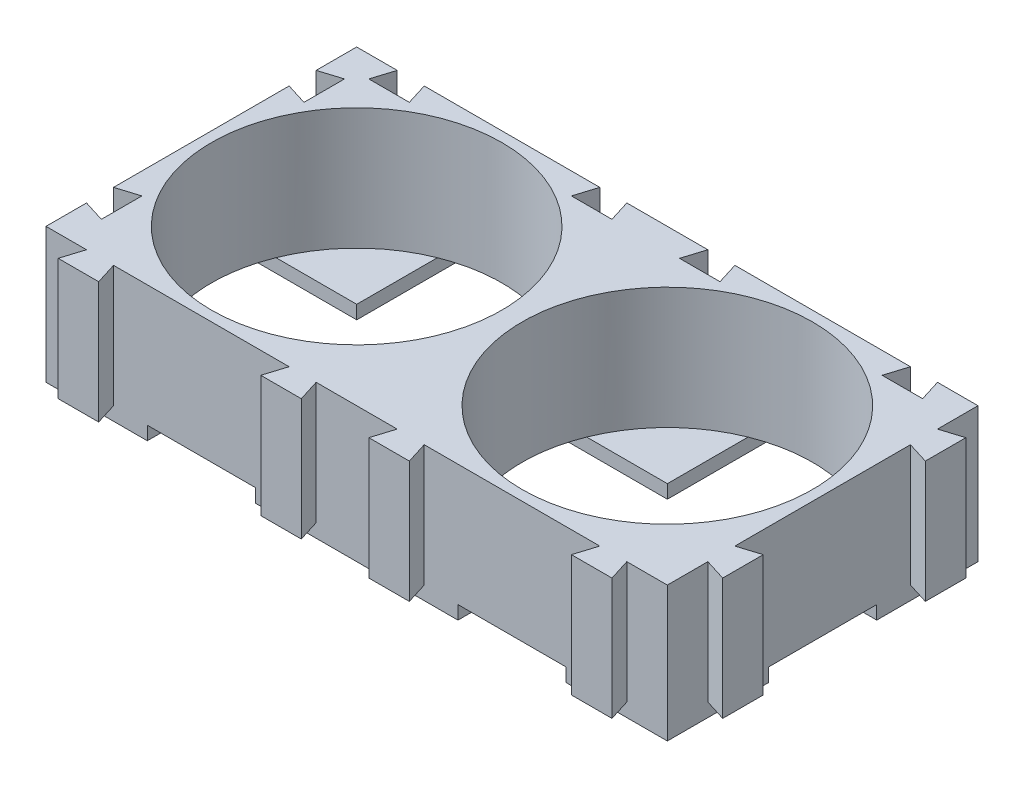
SolidWorks part; units mm, degrees
ref_plane "Front Plane" through (0, 0, 0) normal (0, 0, 1) x (1, 0, 0)
ref_plane "Top Plane" through (0, 0, 0) normal (0, 1, 0) x (1, 0, 0)
ref_plane "Right Plane" through (0, 0, 0) normal (1, 0, 0) x (0, 0, -1)
sketch "Sketch1" plane through (0, 0, 0) normal (0, 1, 0) x (1, 0, 0)
  line L1 (0, 0) -> (47.6, 0)
  line L2 (0, 0) -> (0, 24.6)
  line L3 (0, 24.6) -> (47.6, 24.6)
  line L4 (47.6, 0) -> (47.6, 24.6)
  dimension "D1" = 47.6
  dimension "D2" = 24.6
extrude "Boss-Extrude1" add sketch "Sketch1" along normal blind 10
sketch "Sketch2" plane through (0, 10, 0) normal (0, 1, 0) x (1, 0, 0)
  line L0 (0, -5.5) -> (0, 5.5) construction
  line L1 (47.6, 0) -> (47.6, 24.6) construction
  line L3 (47.6, 24.6) -> (0, 24.6) construction
  circle A0 centre (11.5, 13.1) radius 10.75
  circle A1 centre (34.5, 13.1) radius 10.75
  dimension "D1" = 21.5
  dimension "D2" = 21.5
  dimension "D3" = 23
  dimension "D4" = 11.5
  dimension "D5" = 13.1
  dimension "D6" = 11.5
extrude "Cut-Extrude1" cut sketch "Sketch2" against normal blind 9
sketch "Sketch3" plane through (0, 10, 0) normal (0, 1, 0) x (1, 0, 0)
  line L0 (0, 24.6) -> (0, -11.4) construction
  line L1 (0, -5.5) -> (0, 5.5) construction
  line L2 (47.6, 24.6) -> (0, 24.6) construction
  line L9 (3, 24.6) -> (2.5, 23)
  line L10 (2.5, 23) -> (5.5, 23)
  line L11 (5.5, 23) -> (5, 24.6)
  line L12 (5, 24.6) -> (3, 24.6)
  line L13 (18, 24.6) -> (17.5, 23)
  line L14 (17.5, 23) -> (20.5, 23)
  line L15 (20.5, 23) -> (20, 24.6)
  line L16 (20, 24.6) -> (18, 24.6)
  line L17 (26, 24.6) -> (25.5, 23)
  line L18 (25.5, 23) -> (28.5, 23)
  line L19 (28.5, 23) -> (28, 24.6)
  line L20 (28, 24.6) -> (26, 24.6)
  line L21 (41, 24.6) -> (40.5, 23)
  line L22 (40.5, 23) -> (43.5, 23)
  line L23 (43.5, 23) -> (43, 24.6)
  line L24 (43, 24.6) -> (41, 24.6)
  line L25 (0, 21.6) -> (1.6, 22.1)
  line L26 (1.6, 22.1) -> (1.6, 19.1)
  line L27 (1.6, 19.1) -> (0, 19.6)
  line L28 (0, 19.6) -> (0, 21.6)
  line L29 (0, 6.6) -> (1.6, 7.1)
  line L30 (1.6, 7.1) -> (1.6, 4.1)
  line L31 (1.6, 4.1) -> (0, 4.6)
  line L32 (0, 4.6) -> (0, 6.6)
  dimension "D1" = 2
  dimension "D2" = 3
  dimension "D3" = 0.5
  dimension "D4" = 1.6
  dimension "D5" = 3
  dimension "D6" = 13
  dimension "D7" = 2
  dimension "D8" = 3
  dimension "D9" = 0.5
  dimension "D10" = 1.6
  dimension "D11" = 6
  dimension "D12" = 2
  dimension "D13" = 3
  dimension "D14" = 0.5
  dimension "D15" = 1.6
  dimension "D16" = 13
  dimension "D17" = 2
  dimension "D18" = 3
  dimension "D19" = 0.5
  dimension "D20" = 1.6
  dimension "D21" = 3
  dimension "D22" = 2
  dimension "D23" = 0.5
  dimension "D24" = 1.6
  dimension "D25" = 3
  dimension "D26" = 3
  dimension "D27" = 2
  dimension "D28" = 0.5
  dimension "D29" = 1.6
  dimension "D30" = 13
extrude "Cut-Extrude2" cut sketch "Sketch3" against normal blind 9
sketch "Sketch5" plane through (0, 10, 0) normal (0, 1, 0) x (1, 0, 0)
  line L0 (-5.5, 0) -> (5.5, 0) construction
  line L1 (47.6, 24.6) -> (46, 24.6)
  line L2 (47.6, 24.6) -> (47.6, 0)
  line L3 (47.6, 0) -> (46, 0)
  line L4 (46, 24.6) -> (46, 0)
  dimension "D1" = 1.6
extrude "Cut-Extrude3" cut sketch "Sketch5" against normal blind 10
sketch "Sketch6" plane through (0, 10, 0) normal (0, 1, 0) x (1, 0, 0)
  line L0 (46, 24.6) -> (46, 0) construction
  line L1 (0, 0) -> (46, 0)
  line L2 (0, 0) -> (0, 1.6)
  line L3 (0, 1.6) -> (46, 1.6)
  line L4 (46, 0) -> (46, 1.6)
  dimension "D1" = 1.6
extrude "Cut-Extrude4" cut sketch "Sketch6" against normal blind 10
sketch "Sketch7" plane through (0, 10, 0) normal (0, 1, 0) x (1, 0, 0)
  line L0 (46, 21.6) -> (47.6, 22.1)
  line L1 (46, 24.6) -> (46, 1.6) construction
  line L2 (47.6, 22.1) -> (47.6, 19.1)
  line L3 (47.6, 19.1) -> (46, 19.6)
  line L4 (46, 19.6) -> (46, 21.6)
  line L9 (46, 6.6) -> (47.6, 7.1)
  line L10 (47.6, 7.1) -> (47.6, 4.1)
  line L11 (47.6, 4.1) -> (46, 4.6)
  line L12 (46, 4.6) -> (46, 6.6)
  line L13 (3, 1.6) -> (2.5, 0)
  line L14 (46, 1.6) -> (0, 1.6) construction
  line L15 (-5.5, 0) -> (5.5, 0) construction
  line L16 (2.5, 0) -> (5.5, 0)
  line L17 (5.5, 0) -> (5, 1.6)
  line L18 (5, 1.6) -> (3, 1.6)
  line L19 (0, -5.5) -> (0, 5.5) construction
  line L20 (18, 1.6) -> (17.5, 0)
  line L21 (17.5, 0) -> (20.5, 0)
  line L22 (20.5, 0) -> (20, 1.6)
  line L23 (20, 1.6) -> (18, 1.6)
  line L24 (26, 1.6) -> (25.5, 0)
  line L25 (25.5, 0) -> (28.5, 0)
  line L26 (28.5, 0) -> (28, 1.6)
  line L27 (28, 1.6) -> (26, 1.6)
  line L28 (41, 1.6) -> (40.5, 0)
  line L29 (40.5, 0) -> (43.5, 0)
  line L30 (43.5, 0) -> (43, 1.6)
  line L31 (43, 1.6) -> (41, 1.6)
  dimension "D1" = 3
  dimension "D2" = 2
  dimension "D3" = 0.5
  dimension "D4" = 1.6
  dimension "D5" = 3
  dimension "D6" = 13
  dimension "D7" = 2
  dimension "D8" = 3
  dimension "D9" = 0.5
  dimension "D10" = 1.6
  dimension "D11" = 3
  dimension "D12" = 2
  dimension "D13" = 3
  dimension "D14" = 0.5
  dimension "D15" = 1.6
  dimension "D16" = 2
  dimension "D17" = 3
  dimension "D18" = 0.5
  dimension "D19" = 1.6
  dimension "D20" = 13
  dimension "D21" = 2
  dimension "D22" = 3
  dimension "D23" = 0.5
  dimension "D24" = 6
  dimension "D25" = 2
  dimension "D26" = 3
  dimension "D27" = 0.5
  dimension "D28" = 13
extrude "Boss-Extrude2" add sketch "Sketch7" against normal blind 9
sketch "Sketch10" plane through (0, 0, 0) normal (0, -1, 0) x (1, 0, 0)
  line L0 (0, -5.5) -> (0, 5.5) construction
  line L1 (0, -9.1) -> (46, -9.1)
  line L2 (0, -9.1) -> (0, -17.1039)
  line L3 (0, -17.1039) -> (46, -17.1039)
  line L4 (46, -9.1) -> (46, -17.1039)
  line L5 (46, -24.6) -> (46, -1.6) construction
  line L7 (46, -1.6) -> (0, -1.6) construction
  dimension "D1" = 8.0039
  dimension "D2" = 7.5
extrude "Cut-Extrude5" cut sketch "Sketch10" against normal blind 1
sketch "Sketch11" plane through (0, 0, 0) normal (0, -1, 0) x (1, 0, 0)
  line L0 (46, -1.6) -> (0, -1.6) construction
  line L1 (7.5, -1.6) -> (15.5, -1.6)
  line L2 (7.5, -1.6) -> (7.5, -24.6)
  line L3 (7.5, -24.6) -> (15.5, -24.6)
  line L4 (15.5, -1.6) -> (15.5, -24.6)
  line L5 (46, -24.6) -> (0, -24.6) construction
  line L6 (0, -5.5) -> (0, 5.5) construction
  line L8 (30.5, -1.6) -> (38.5, -1.6)
  line L9 (30.5, -1.6) -> (30.5, -24.6)
  line L10 (30.5, -24.6) -> (38.5, -24.6)
  line L11 (38.5, -1.6) -> (38.5, -24.6)
  dimension "D1" = 8
  dimension "D2" = 7.5
  dimension "D3" = 8
  dimension "D4" = 7.5
extrude "Cut-Extrude6" cut sketch "Sketch11" against normal blind 1
